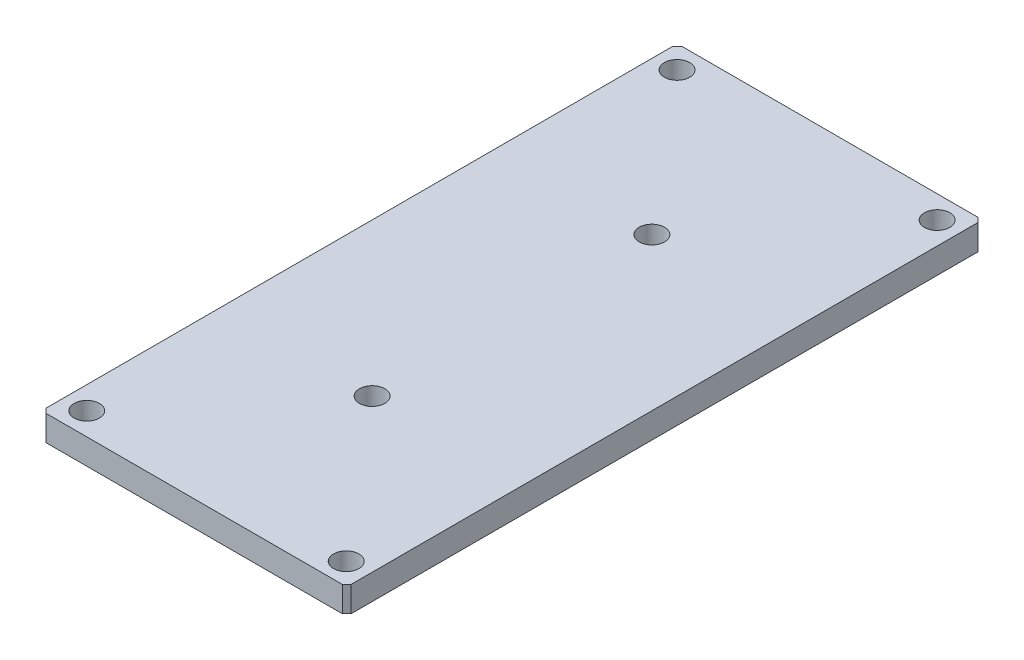
SolidWorks part; units mm, degrees
ref_plane "前视基准面" through (0, 0, 0) normal (0, 0, 1) x (1, 0, 0)
ref_plane "上视基准面" through (0, 0, 0) normal (0, 1, 0) x (1, 0, 0)
ref_plane "右视基准面" through (0, 0, 0) normal (1, 0, 0) x (0, 0, -1)
other "Configuration Table"
sketch "草图1" plane through (0, 0, 0) normal (0, 1, 0) x (1, 0, 0)
  line L1 (0.1142, 24.2086) -> (-23.8858, 24.2086)
  line L2 (0.1142, 24.2086) -> (0.1142, 74.2086)
  line L3 (0.1142, 74.2086) -> (-23.8858, 74.2086)
  line L4 (-23.8858, 24.2086) -> (-23.8858, 74.2086)
  circle A0 centre (-11.8858, 60.2086) radius 1
extrude "凸台-拉伸1" add sketch "草图1" along normal blind 2
sketch "草图2" plane through (0, 2, 0) normal (0, 1, 0) x (1, 0, 0)
  circle A0 centre (-11.8858, 38.2086) radius 1
  circle A1 centre (-22.1098, 72.4126) radius 1
  circle A2 centre (-1.6558, 72.4126) radius 1
  circle A3 centre (-22.1078, 25.9866) radius 1
  circle A4 centre (-1.6558, 25.9386) radius 1
extrude "切除-拉伸2" cut sketch "草图2" against normal blind 2
sketch "草图3" plane through (0, 2, 0) normal (0, 1, 0) x (1, 0, 0)
  line L0 (-23.8858, 74.2086) -> (-23.5358, 74.2086)
  line L1 (0.1142, 74.2086) -> (-23.8858, 74.2086) construction
  line L2 (-23.8858, 74.2086) -> (-23.8858, 73.8586)
  line L3 (-23.8858, 74.2086) -> (-23.8858, 24.2086) construction
  line L4 (-23.8858, 73.8586) -> (-23.5358, 74.2086)
  line L5 (0.1142, 74.2086) -> (0.1142, 73.8586)
  line L6 (0.1142, 24.2086) -> (0.1142, 74.2086) construction
  line L8 (0.1142, 74.2086) -> (-0.2358, 74.2086)
  line L9 (-0.2358, 74.2086) -> (0.1142, 73.8586)
  line L10 (0.1142, 24.2086) -> (-0.2358, 24.2086)
  line L11 (-23.8858, 24.2086) -> (0.1142, 24.2086) construction
  line L13 (0.1142, 24.2086) -> (0.1142, 24.5586)
  line L14 (0.1142, 24.5586) -> (-0.2358, 24.2086)
  line L15 (-23.8858, 24.2086) -> (-23.5358, 24.2086)
  line L17 (-23.8858, 24.5586) -> (-23.5358, 24.2086)
  line L18 (-23.8858, 24.5586) -> (-23.8858, 24.2086)
extrude "切除-拉伸3" cut sketch "草图3" against normal blind 2
